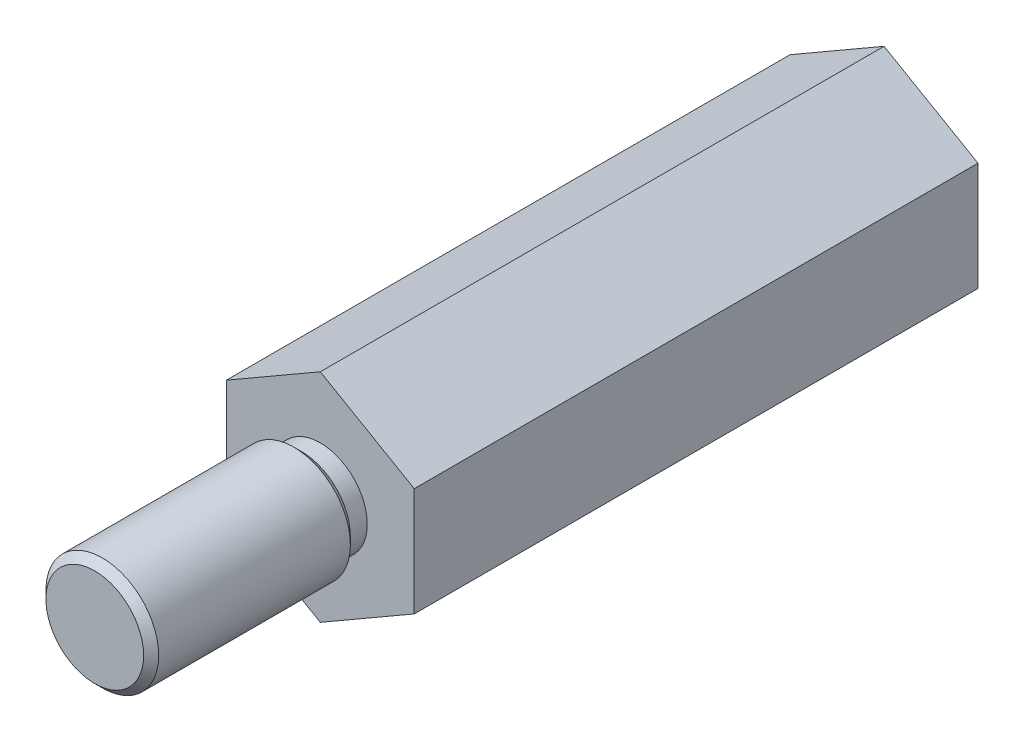
SolidWorks part; units mm, degrees
ref_plane "Спереди" through (0, 0, 0) normal (0, 0, 1) x (1, 0, 0)
ref_plane "Сверху" through (0, 0, 0) normal (0, 1, 0) x (1, 0, 0)
ref_plane "Справа" through (0, 0, 0) normal (1, 0, 0) x (0, 0, -1)
sketch "Эскиз1" plane through (0, 0, 0) normal (0, 0, 1) x (1, 0, 0)
  line L1 (0, 2.8868) -> (-2.5, 1.4434)
  line L2 (-2.5, 1.4434) -> (-2.5, -1.4434)
  line L3 (-2.5, -1.4434) -> (0, -2.8868)
  line L4 (0, -2.8868) -> (2.5, -1.4434)
  line L5 (2.5, -1.4434) -> (2.5, 1.4434)
  line L6 (2.5, 1.4434) -> (0, 2.8868)
  circle A0 centre (0, 0) radius 2.5 construction
  dimension "D1" = 5
extrude "Вытянуть1" add sketch "Эскиз1" along normal blind 15
sketch "Эскиз2" plane through (0, 0, 15) normal (0, 0, 1) x (1, 0, 0)
  circle A0 centre (0, 0) radius 1.5
  dimension "D1" = 3
extrude "Вытянуть2" add sketch "Эскиз2" along normal blind 6
cosmetic thread "Условное изображение резьбы2"
sketch "Эскиз3" plane through (0, 0, 15) normal (0, 0, 1) x (1, 0, 0)
  circle A0 centre (0, 0) radius 1.25
  circle A1 centre (0, 0) radius 1.5 construction
  circle A2 centre (0, 0) radius 1.5
  dimension "D1" = 2.5
extrude "Вырез-Вытянуть3" cut sketch "Эскиз3" along normal blind 0.5
chamfer "Фаска1" distance 0.2 angle 45 2 edges at (1.5, 0, 15.5) (1.5, 0, 21)
hole_wizard "M4 Clearance Hole1" positions "Трехмерный эскиз2" profile "Эскиз5" hole size "M4" standard "Ansi Metric"
sketch3d "Трехмерный эскиз2"
  point P0 (0, 0, 0)
  point P2 (0, 0, 0)
  point P3 (0, 0, 0)
sketch "Эскиз5" plane through (0, 0, 0) normal (1, 0, 0) x (0, 1, 0)
  line L0 (0, 0) -> (0, 6.7511)
  line L1 (0, 6.7511) -> (1.25, 6)
  line L2 (1.25, 6) -> (1.25, 0.25)
  line L3 (1.25, 0.25) -> (1.5, 0)
  line L5 (1.5, 0) -> (0, 0)
  line L6 (-1.25, 0.25) -> (-1.5, 0) construction
  line L10 (0, 6.7511) -> (-1.25, 6) construction
  line L11 (0, -6.35) -> (0, 107.95) construction
  dimension "Диаметр отверстия" = 2.5
  dimension "Глубина отверстия" = 6
  dimension "Диаметр передней зенковки" = 3
  dimension "Угол передней зенковки" = 90
  dimension "Угол заточки сверла" = 118
cosmetic thread "Условное изображение резьбы1" parameters "D1"=5, "D2"=3
